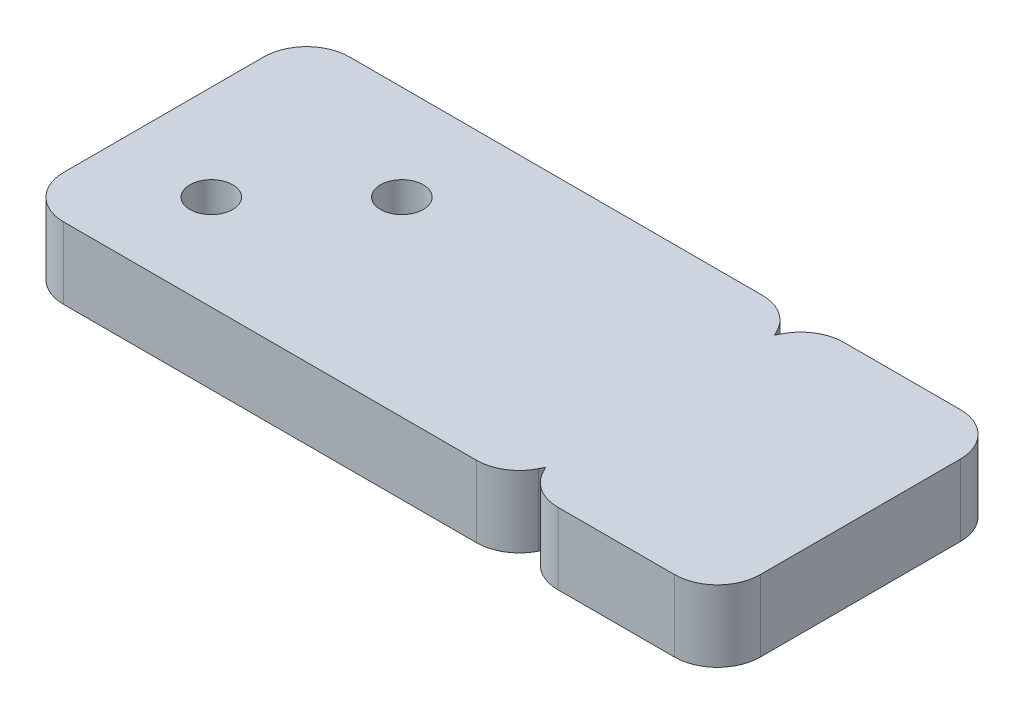
SolidWorks part; units mm, degrees
ref_plane "Front Plane" through (0, 0, 0) normal (0, 0, 1) x (1, 0, 0)
ref_plane "Top Plane" through (0, 0, 0) normal (0, 1, 0) x (1, 0, 0)
ref_plane "Right Plane" through (0, 0, 0) normal (1, 0, 0) x (0, 0, -1)
sketch "Sketch1" plane through (0, 0, 0) normal (0, 1, 0) x (1, 0, 0)
  line L0 (-65.8878, 11.5948) -> (-65.8878, -13.8052)
  line L1 (-65.8878, -13.8052) -> (-23.038, -13.8052)
  line L2 (-3.9753, -13.8052) -> (-3.9753, 11.5948)
  line L3 (-3.9753, 11.5948) -> (-20.498, 11.5948)
  line L5 (-23.038, 11.5948) -> (-65.8878, 11.5948)
  line L6 (-21.768, -11.2652) -> (-20.498, -13.8052)
  line L7 (-21.768, -11.2652) -> (-23.038, -13.8052)
  line L8 (-21.768, 9.0548) -> (-23.038, 11.5948)
  line L9 (-21.768, 9.0548) -> (-20.498, 11.5948)
  line L10 (-20.498, -13.8052) -> (-3.9753, -13.8052)
  circle A3 centre (-57.4219, -5.3393) radius 1.905
  circle A4 centre (-48.9531, 3.1294) radius 1.905
  point P6 (0, 0)
  point P12 (0, 0)
extrude "Boss-Extrude3" add sketch "Sketch1" along normal blind 6.35
fillet "Fillet4" radius 3.81 8 edges at (-3.9753, 3.175, -11.5948) (-20.498, 3.175, -11.5948) (-23.038, 3.175, -11.5948) (-65.8878, 3.175, -11.5948) (-3.9753, 3.175, 13.8052) (-20.498, 3.175, 13.8052) (-23.038, 3.175, 13.8052) (-65.8878, 3.175, 13.8052)
